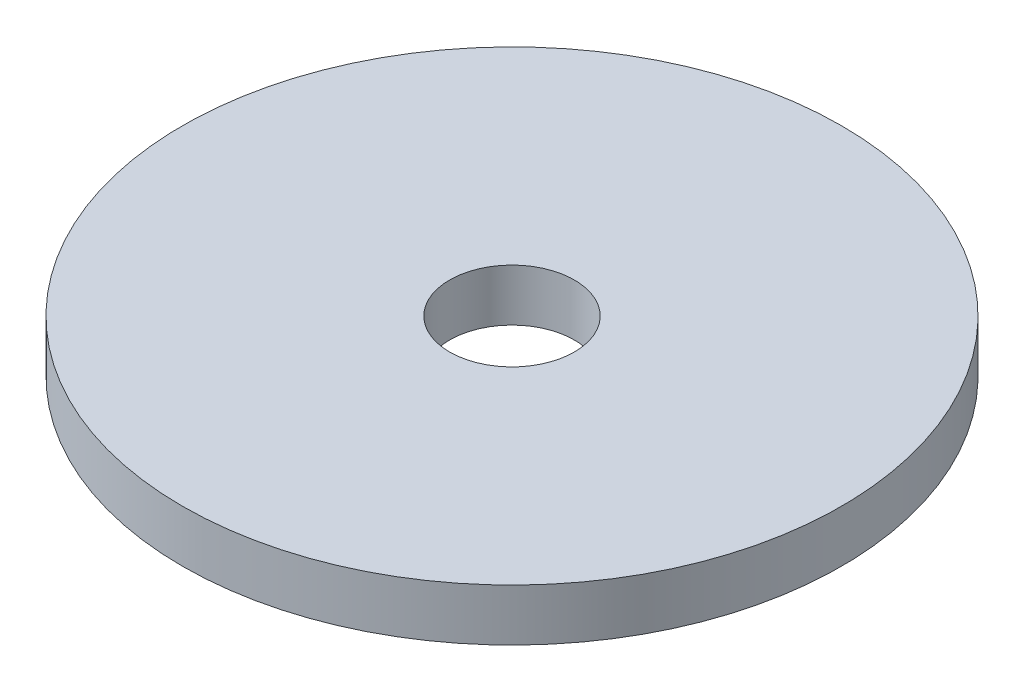
SolidWorks part; units mm, degrees
ref_plane "Front Plane" through (0, 0, 0) normal (0, 0, 1) x (1, 0, 0)
ref_plane "Top Plane" through (0, 0, 0) normal (0, 1, 0) x (1, 0, 0)
ref_plane "Right Plane" through (0, 0, 0) normal (1, 0, 0) x (0, 0, -1)
sketch "Sketch1" plane through (0, 0, 0) normal (0, 1, 0) x (1, 0, 0)
  circle A0 centre (0, 0) radius 15.845
  circle A1 centre (0, 0) radius 3
  dimension "D1" = 31.69
  dimension "D2" = 6
extrude "Boss-Extrude1" add sketch "Sketch1" along normal blind 2.5
